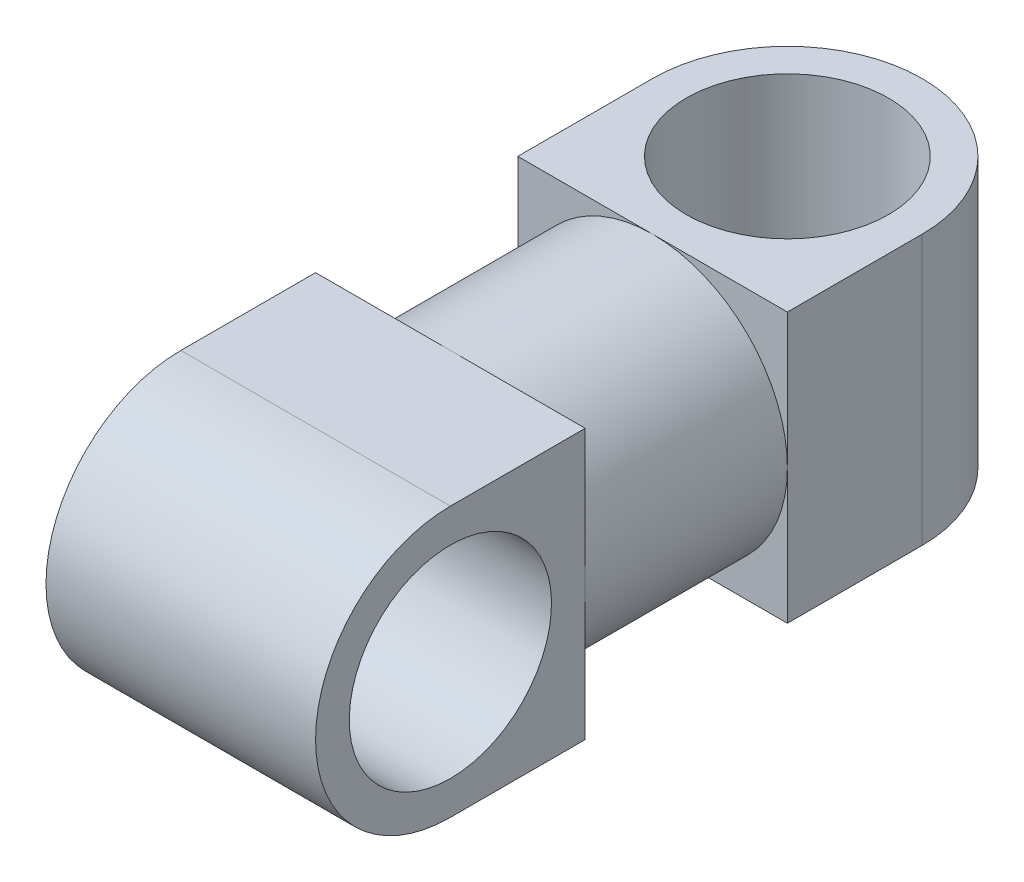
SolidWorks part; units mm, degrees
ref_plane "Front Plane" through (0, 0, 0) normal (0, 0, 1) x (1, 0, 0)
ref_plane "Top Plane" through (0, 0, 0) normal (0, 1, 0) x (1, 0, 0)
ref_plane "Right Plane" through (0, 0, 0) normal (1, 0, 0) x (0, 0, -1)
sketch "Sketch1" plane through (0, 0, 0) normal (0, 1, 0) x (1, 0, 0)
  line L1 (-20, -20) -> (20, -20)
  line L2 (-20, -20) -> (-20, 0)
  line L4 (20, -20) -> (20, 0)
  circle A1 centre (0, 0) radius 15
  arc A2 (20, 0) -> (-20, 0) centre (0, 0) ccw
  point P0 (0, 0)
extrude "Boss-Extrude1" add sketch "Sketch1" along normal blind 40
sketch "Sketch2" plane through (0, 0, 0) normal (0, 0, 1) x (1, 0, 0)
  circle A0 centre (0, 20) radius 20
extrude "Boss-Extrude2" add sketch "Sketch2" along normal blind 30 from offset 20
ref_plane "Plane1" through (-20, 0, 0) normal (-1, 0, 0) x (0, 0, 1)
sketch "Sketch3" plane through (-20, 0, 0) normal (-1, 0, 0) x (0, 0, 1)
  line L0 (50, 40.0559) -> (50, 0.0559)
  line L1 (50, 40.0559) -> (70, 40.0559)
  line L2 (50, 0.0559) -> (70, 0.0559)
  circle A0 centre (70, 20.0559) radius 15
  arc A1 (70, 0.0559) -> (70, 40.0559) centre (70, 20.0559) ccw
  point P0 (70, 20.0559)
extrude "Boss-Extrude3" add sketch "Sketch3" against normal blind 40
